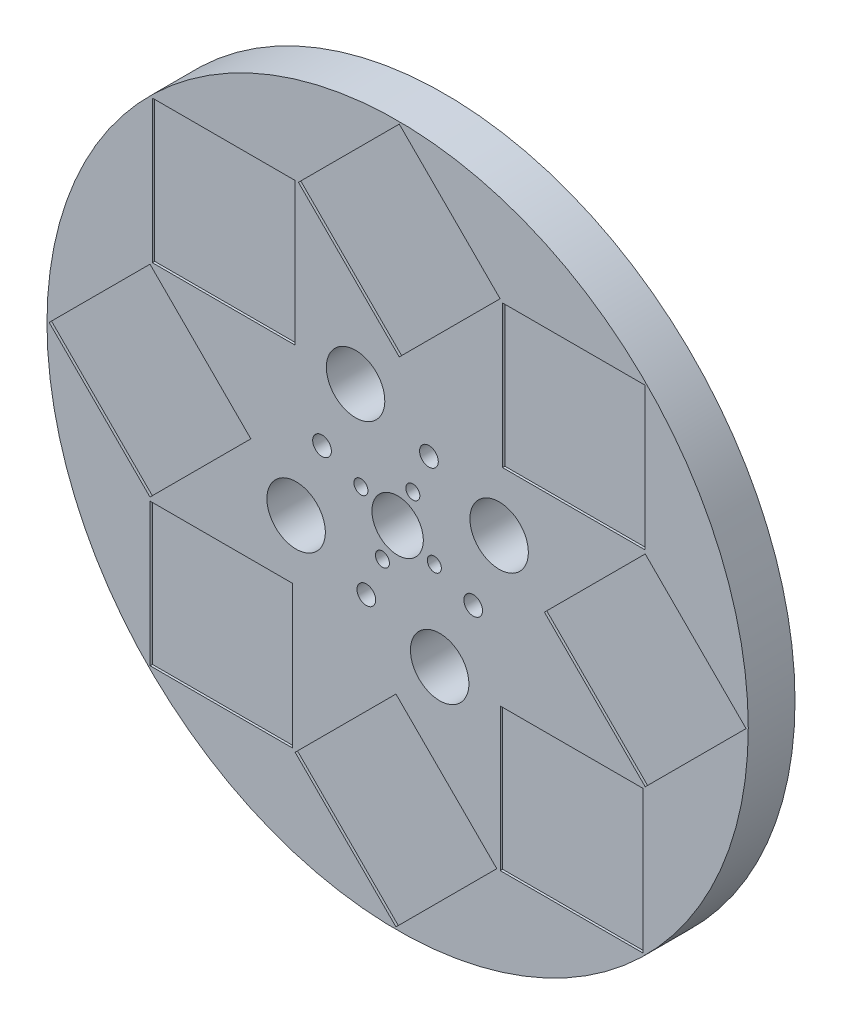
SolidWorks part; units mm, degrees
material "1.0545 (S355N)"
ref_plane "Ön Düzlem" through (0, 0, 0) normal (0, 0, 1) x (1, 0, 0)
ref_plane "Üst Düzlem" through (0, 0, 0) normal (0, 1, 0) x (1, 0, 0)
ref_plane "Sağ Düzlem" through (0, 0, 0) normal (1, 0, 0) x (0, 0, -1)
sketch "Sketch1" plane through (0, 0, 0) normal (0, 0, 1) x (1, 0, 0)
  circle A0 centre (0, 0) radius 150
  circle A1 centre (0, 0) radius 11
  dimension "c1" = 300
  dimension "c2" = 22
extrude "Boss-Extrude1" add sketch "Sketch1" along normal blind 20 contours A0 | A1
sketch "Sketch2" plane through (0, 0, 0) normal (0, 0, 1) x (1, 0, 0)
  line L0 (0, 0) -> (72.3642, 0) construction
  line L1 (0, 0) -> (70.6348, -29.2579) construction
  line L2 (0, 0) -> (74.2627, 30.7606) construction
  circle A0 centre (0, 0) radius 17 construction
  circle A1 centre (0, 0) radius 35 construction
  circle A2 centre (0, 0) radius 47 construction
  circle A3 centre (43.4223, 17.9861) radius 12.5
  dimension "D1" = 34
  dimension "D2" = 70
  dimension "D4" = 94
  dimension "D6" = 25
  dimension "D3" = 22.5
  dimension "D5" = 22.5
hole_wizard "Ø6.0mm Dowel Hole1" positions "Sketch7" profile "Sketch8" hole size "Ø6.0" standard "ANSI Metric" end condition through all
sketch "Sketch7" plane through (0, 0, 0) normal (0, 0, -1) x (-1, 0, 0)
  line L0 (0, 0) -> (-86.5137, 0) construction
  line L2 (0, 0) -> (-61.4755, -25.464) construction
  circle A0 centre (0, 0) radius 17 construction
  point P0 (-15.706, -6.5056)
  dimension "D1" = 22.5
sketch "Sketch8" plane through (15.706, -6.5056, 0) normal (1, 0, 0) x (0, 1, 0)
  line L0 (0, 0) -> (0, 20)
  line L1 (0, 20) -> (3, 20)
  line L2 (3, 20) -> (3, 0)
  line L5 (3, 0) -> (0, 0)
  line L11 (0, -6.35) -> (0, 107.95) construction
  dimension "Thru Hole Dia." = 6
  dimension "Thru Hole Depth" = 20
hole_wizard "Ø8.0mm Dowel Hole1" positions "Sketch10" profile "Sketch11" hole size "Ø8.0" standard "ANSI Metric" end condition through all
sketch "Sketch10" plane through (0, 0, 0) normal (0, 0, -1) x (-1, 0, 0)
  line L0 (184775.9065, 76536.6865) -> (-184846.5413, -76565.9444) construction
  circle A0 centre (0, 0) radius 35 construction
  point P0 (-32.3358, -13.3939)
sketch "Sketch11" plane through (32.3358, -13.3939, 0) normal (1, 0, 0) x (0, 1, 0)
  line L0 (0, 0) -> (0, 20)
  line L1 (0, 20) -> (4, 20)
  line L2 (4, 20) -> (4, 0)
  line L5 (4, 0) -> (0, 0)
  line L11 (0, -6.35) -> (0, 107.95) construction
  dimension "Thru Hole Dia." = 8
  dimension "Thru Hole Depth" = 20
pattern_circular "CirPattern2" count 4 over 360 about axis through (0, 0, 0) along (0, 0, 1) of "Ø6.0mm Dowel Hole1", "Ø8.0mm Dowel Hole1"
sketch "Sketch9" plane through (0, 0, 20) normal (0, 0, 1) x (1, 0, 0)
  line L0 (0, 148.3528) -> (-42.4264, 105.9264)
  line L1 (-42.4264, 105.9264) -> (0, 63.5)
  line L2 (0, 63.5) -> (42.4264, 105.9264)
  line L3 (42.4264, 105.9264) -> (0, 148.3528)
  line L4 (-42.4264, 105.9264) -> (0.7071, 62.7929)
  line L5 (-42.4264, 105.9264) -> (0.7071, 149.0599)
  line L6 (0.7071, 62.7929) -> (43.8406, 105.9264)
  line L7 (0.7071, 149.0599) -> (43.8406, 105.9264)
  circle A0 centre (0, 0) radius 11 construction
  dimension "D3" = 63.5
  dimension "D1" = 60
  dimension "D2" = 60
  dimension "D4" = 61
  dimension "D5" = 61
extrude "Cut-Extrude2" cut sketch "Sketch9" against normal blind 1 contours L4 L6 L7 L5
pattern_circular "CirPattern3" count 8 over 360 about axis through (0, 0, 0) along (0, 0, 1) of "Cut-Extrude2"
extrude "Cut-Extrude4" cut sketch "Sketch2" along normal through all contours A3
pattern_circular "CirPattern4" count 4 over 360 about axis through (0, 0, 0) along (0, 0, 1) of "Cut-Extrude4"
